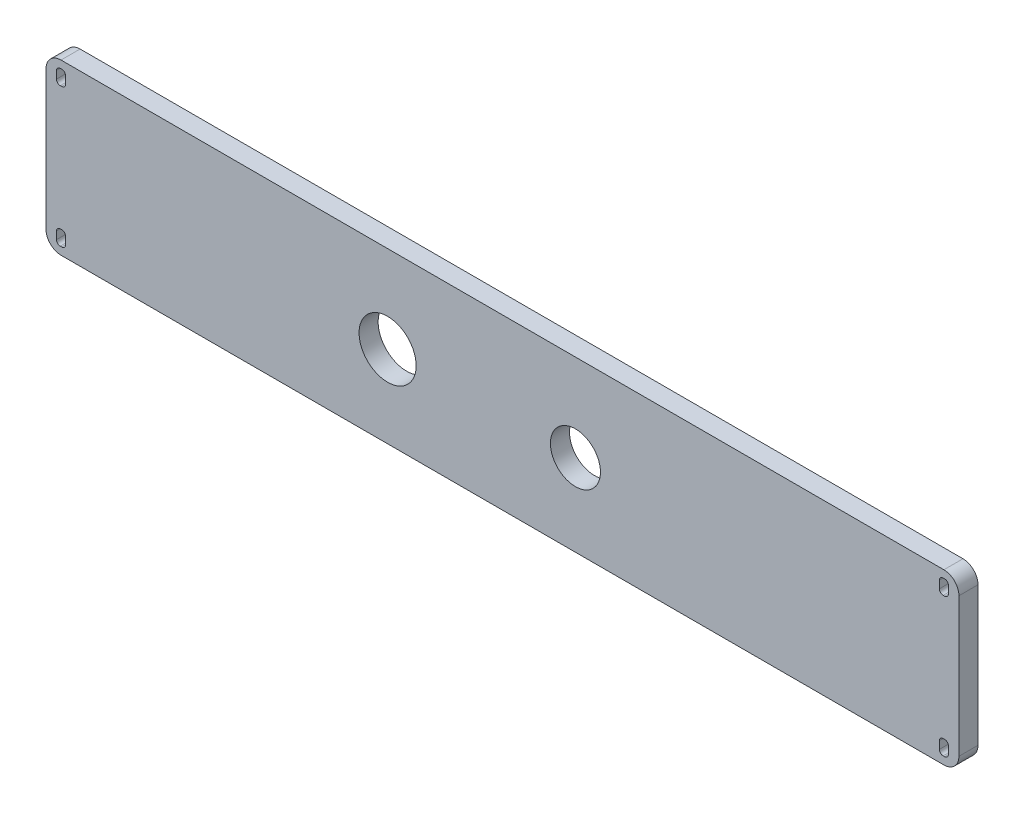
SolidWorks part; units mm, degrees
ref_plane "Front Plane" through (0, 0, 0) normal (0, 0, 1) x (1, 0, 0)
ref_plane "Top Plane" through (0, 0, 0) normal (0, 1, 0) x (1, 0, 0)
ref_plane "Right Plane" through (0, 0, 0) normal (1, 0, 0) x (0, 0, -1)
sketch "Sketch1" plane through (0, 0, 0) normal (0, 0, 1) x (1, 0, 0)
  line L0 (334.3524, 24.5402) -> (333.3524, 24.5402)
  line L1 (-263.7156, 132.0622) -> (343.8524, 132.0622)
  line L2 (-263.7156, 132.0622) -> (-263.7156, 19.5402)
  line L3 (-263.7156, 19.5402) -> (343.8524, 19.5402)
  line L4 (343.8524, 132.0622) -> (343.8524, 19.5402)
  line L5 (336.8524, 27.0402) -> (336.8524, 32.0402)
  line L6 (334.3524, 34.5402) -> (333.3524, 34.5402)
  line L7 (330.8524, 27.0402) -> (330.8524, 32.0402)
  line L8 (333.8524, 34.5402) -> (333.8524, 24.5402) construction
  line L9 (330.8524, 29.5402) -> (336.8524, 29.5402) construction
  line L10 (-253.2176, 24.5402) -> (-254.2176, 24.5402)
  line L11 (-256.7176, 27.0402) -> (-256.7176, 32.0402)
  line L12 (-253.2176, 34.5402) -> (-254.2176, 34.5402)
  line L13 (-250.7176, 27.0402) -> (-250.7176, 32.0402)
  line L14 (-253.2176, 117.0602) -> (-254.2176, 117.0602)
  line L15 (-256.7176, 119.5602) -> (-256.7176, 124.5602)
  line L16 (-253.2176, 127.0602) -> (-254.2176, 127.0602)
  line L17 (-250.7176, 119.5602) -> (-250.7176, 124.5602)
  line L18 (334.3524, 117.0602) -> (333.3524, 117.0602)
  line L19 (330.8524, 119.5602) -> (330.8524, 124.5602)
  line L20 (334.3524, 127.0602) -> (333.3524, 127.0602)
  line L21 (336.8524, 119.5602) -> (336.8524, 124.5602)
  arc A0 (334.3524, 24.5402) -> (336.8524, 27.0402) centre (334.3524, 27.0402) ccw
  arc A1 (336.8524, 32.0402) -> (334.3524, 34.5402) centre (334.3524, 32.0402) ccw
  arc A2 (333.3524, 24.5402) -> (330.8524, 27.0402) centre (333.3524, 27.0402) cw
  arc A3 (333.3524, 34.5402) -> (330.8524, 32.0402) centre (333.3524, 32.0402) ccw
  arc A4 (-254.2176, 24.5402) -> (-256.7176, 27.0402) centre (-254.2176, 27.0402) cw
  arc A5 (-254.2176, 34.5402) -> (-256.7176, 32.0402) centre (-254.2176, 32.0402) ccw
  arc A6 (-250.7176, 32.0402) -> (-253.2176, 34.5402) centre (-253.2176, 32.0402) ccw
  arc A7 (-253.2176, 24.5402) -> (-250.7176, 27.0402) centre (-253.2176, 27.0402) ccw
  arc A8 (-254.2176, 117.0602) -> (-256.7176, 119.5602) centre (-254.2176, 119.5602) cw
  arc A9 (-254.2176, 127.0602) -> (-256.7176, 124.5602) centre (-254.2176, 124.5602) ccw
  arc A10 (-250.7176, 124.5602) -> (-253.2176, 127.0602) centre (-253.2176, 124.5602) ccw
  arc A11 (-253.2176, 117.0602) -> (-250.7176, 119.5602) centre (-253.2176, 119.5602) ccw
  arc A12 (333.3524, 117.0602) -> (330.8524, 119.5602) centre (333.3524, 119.5602) cw
  arc A13 (333.3524, 127.0602) -> (330.8524, 124.5602) centre (333.3524, 124.5602) ccw
  arc A14 (336.8524, 124.5602) -> (334.3524, 127.0602) centre (334.3524, 124.5602) ccw
  arc A15 (334.3524, 117.0602) -> (336.8524, 119.5602) centre (334.3524, 119.5602) ccw
  circle A16 centre (88.6326, 74.0187) radius 16.65
  circle A17 centre (-36.3674, 74.0187) radius 19
  dimension "D5" = 2.5
  dimension "D18" = 33.3
  dimension "D19" = 58.0435
  dimension "D13" = 58.0435
  dimension "D14" = 38
  dimension "D15" = 227.3482
  dimension "D16" = 125
  dimension "D1" = 132.0622
  dimension "23.92in" = 607.568
  dimension "4.4" = 112.522
  dimension "D2" = 343.8524
  dimension "D3" = 6
  dimension "D4" = 10
  dimension "D6" = 10
  dimension "D7" = 10
  dimension "D10" = 7
  dimension "D11" = 5.002
  dimension "D12" = 6.998
  dimension "D8" = 2
  dimension "D9" = 2
extrude "Boss-Extrude1" add sketch "Sketch1" along normal blind 12.7
fillet "Fillet1" radius 10 4 edges at (343.8524, 19.5402, 6.35) (343.8524, 132.0622, 6.35) (-263.7156, 19.5402, 6.35) (-263.7156, 132.0622, 6.35)
